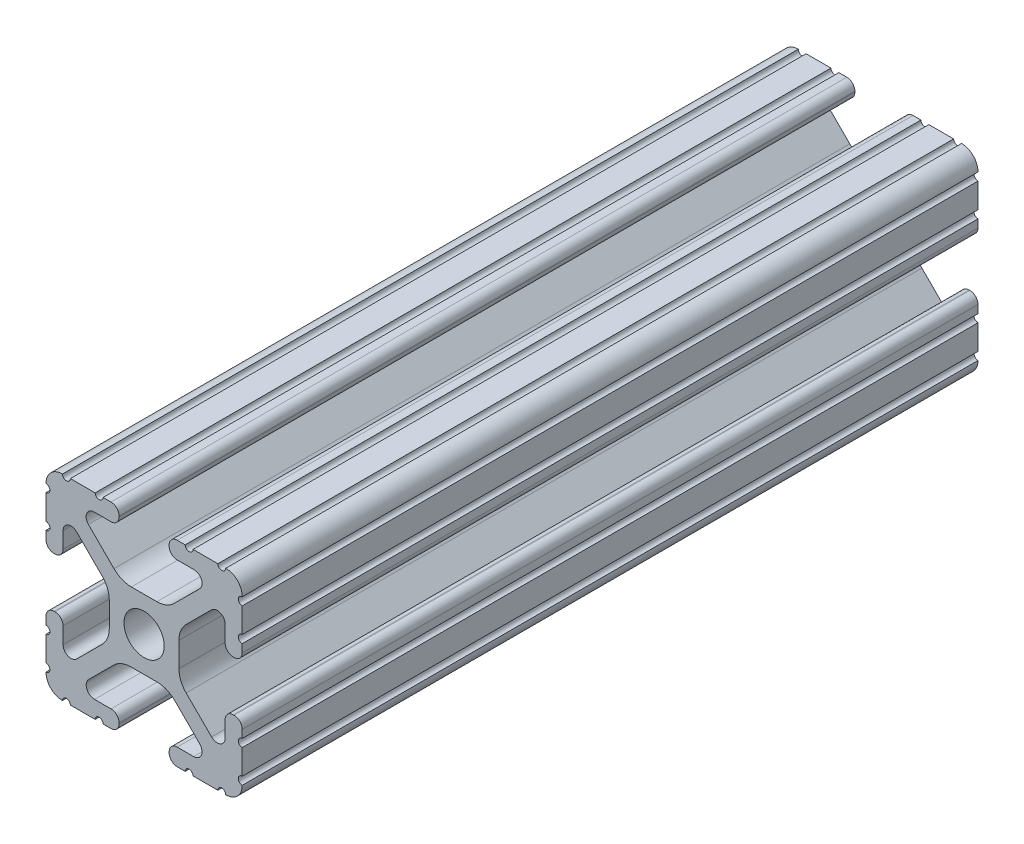
SolidWorks part; units mm, degrees
ref_plane "Front Plane" through (0, 0, 0) normal (0, 0, 1) x (1, 0, 0)
ref_plane "Top Plane" through (0, 0, 0) normal (0, 1, 0) x (1, 0, 0)
ref_plane "Right Plane" through (0, 0, 0) normal (1, 0, 0) x (0, 0, -1)
sketch "Sketch1" plane through (0, 0, 0) normal (0, 0, 1) x (1, 0, 0)
  line L88 (-7.1797, -8.6452) -> (-3.9523, -5.4237)
  line L89 (-1.7093, -4.4958) -> (1.7093, -4.4958)
  line L90 (3.9523, -5.4237) -> (7.1797, -8.6452)
  line L91 (6.4164, -10.4902) -> (4.2875, -10.4902)
  line L92 (3.2385, -11.5392) -> (3.2385, -11.651)
  line L93 (4.2875, -12.7) -> (5.3171, -12.7)
  line L94 (6.3331, -12.7) -> (9.5504, -12.7)
  line L95 (12.7, -9.5504) -> (12.7, -6.3331)
  line L96 (12.7, -5.3171) -> (12.7, -4.2875)
  line L97 (11.651, -3.2385) -> (11.5392, -3.2385)
  line L98 (10.4902, -4.2875) -> (10.4902, -6.4021)
  line L99 (8.7371, -7.1294) -> (5.441, -3.8408)
  line L100 (4.5085, -1.5932) -> (4.5085, 1.5932)
  line L101 (5.441, 3.8408) -> (8.7371, 7.1294)
  line L102 (10.4902, 6.4021) -> (10.4902, 4.2875)
  line L103 (11.5392, 3.2385) -> (11.651, 3.2385)
  line L104 (12.7, 4.2875) -> (12.7, 5.3171)
  line L105 (12.7, 6.3331) -> (12.7, 9.5504)
  line L106 (9.5504, 12.7) -> (6.3331, 12.7)
  line L107 (5.3171, 12.7) -> (4.2875, 12.7)
  line L108 (3.2385, 11.651) -> (3.2385, 11.5392)
  line L109 (4.2875, 10.4902) -> (6.4768, 10.4902)
  line L110 (7.207, 8.7244) -> (3.8983, 5.4232)
  line L111 (1.6558, 4.4958) -> (-1.6558, 4.4958)
  line L112 (-3.8983, 5.4232) -> (-7.207, 8.7244)
  line L113 (-6.4768, 10.4902) -> (-4.2875, 10.4902)
  line L114 (-3.2385, 11.5392) -> (-3.2385, 11.651)
  line L115 (-4.2875, 12.7) -> (-5.3171, 12.7)
  line L116 (-6.3331, 12.7) -> (-9.5504, 12.7)
  line L117 (-12.7, 9.5504) -> (-12.7, 6.3331)
  line L118 (-12.7, 5.3171) -> (-12.7, 4.2875)
  line L119 (-11.651, 3.2385) -> (-11.5392, 3.2385)
  line L120 (-10.4902, 4.2875) -> (-10.4902, 6.4021)
  line L121 (-8.7371, 7.1294) -> (-5.441, 3.8408)
  line L122 (-4.5085, 1.5932) -> (-4.5085, -1.5932)
  line L123 (-5.441, -3.8408) -> (-8.7371, -7.1294)
  line L124 (-10.4902, -6.4021) -> (-10.4902, -4.2875)
  line L125 (-11.5392, -3.2385) -> (-11.651, -3.2385)
  line L126 (-12.7, -4.2875) -> (-12.7, -5.3171)
  line L127 (-12.7, -6.3331) -> (-12.7, -9.5504)
  line L128 (-9.5504, -12.7) -> (-6.3331, -12.7)
  line L129 (-5.3171, -12.7) -> (-4.2875, -12.7)
  line L130 (-3.2385, -11.651) -> (-3.2385, -11.5392)
  line L131 (-4.2875, -10.4902) -> (-6.4164, -10.4902)
  circle A1 centre (0, 0) radius 2.6035
  arc A104 (-7.1797, -8.6452) -> (-6.4164, -10.4902) centre (-6.4164, -9.4098) ccw
  arc A105 (-1.7093, -4.4958) -> (-3.9523, -5.4237) centre (-1.7093, -7.6708) ccw
  arc A106 (3.9523, -5.4237) -> (1.7093, -4.4958) centre (1.7093, -7.6708) ccw
  arc A107 (6.4164, -10.4902) -> (7.1797, -8.6452) centre (6.4164, -9.4098) ccw
  arc A108 (4.2875, -10.4902) -> (3.2385, -11.5392) centre (4.2875, -11.5392) ccw
  arc A109 (3.2385, -11.651) -> (4.2875, -12.7) centre (4.2875, -11.651) ccw
  arc A110 (6.3331, -12.7) -> (5.3171, -12.7) centre (5.8251, -12.7) ccw
  arc A111 (10.5664, -12.6998) -> (9.5504, -12.7) centre (10.0584, -12.7) ccw
  arc A112 (10.5664, -12.6998) -> (12.6998, -10.5664) centre (10.5918, -10.5918) ccw
  arc A113 (12.7, -9.5504) -> (12.6998, -10.5664) centre (12.7, -10.0584) ccw
  arc A114 (12.7, -5.3171) -> (12.7, -6.3331) centre (12.7, -5.8251) ccw
  arc A115 (12.7, -4.2875) -> (11.651, -3.2385) centre (11.651, -4.2875) ccw
  arc A116 (11.5392, -3.2385) -> (10.4902, -4.2875) centre (11.5392, -4.2875) ccw
  arc A117 (8.7371, -7.1294) -> (10.4902, -6.4021) centre (9.4628, -6.4021) ccw
  arc A118 (4.5085, -1.5932) -> (5.441, -3.8408) centre (7.6835, -1.5932) ccw
  arc A119 (5.441, 3.8408) -> (4.5085, 1.5932) centre (7.6835, 1.5932) ccw
  arc A120 (10.4902, 6.4021) -> (8.7371, 7.1294) centre (9.4628, 6.4021) ccw
  arc A121 (10.4902, 4.2875) -> (11.5392, 3.2385) centre (11.5392, 4.2875) ccw
  arc A122 (11.651, 3.2385) -> (12.7, 4.2875) centre (11.651, 4.2875) ccw
  arc A123 (12.7, 6.3331) -> (12.7, 5.3171) centre (12.7, 5.8251) ccw
  arc A124 (12.6998, 10.5664) -> (12.7, 9.5504) centre (12.7, 10.0584) ccw
  arc A125 (12.6998, 10.5664) -> (10.5664, 12.6998) centre (10.5918, 10.5918) ccw
  arc A126 (9.5504, 12.7) -> (10.5664, 12.6998) centre (10.0584, 12.7) ccw
  arc A127 (5.3171, 12.7) -> (6.3331, 12.7) centre (5.8251, 12.7) ccw
  arc A128 (4.2875, 12.7) -> (3.2385, 11.651) centre (4.2875, 11.651) ccw
  arc A129 (3.2385, 11.5392) -> (4.2875, 10.4902) centre (4.2875, 11.5392) ccw
  arc A130 (7.207, 8.7244) -> (6.4768, 10.4902) centre (6.4768, 9.4563) ccw
  arc A131 (1.6558, 4.4958) -> (3.8983, 5.4232) centre (1.6558, 7.6708) ccw
  arc A132 (-3.8983, 5.4232) -> (-1.6558, 4.4958) centre (-1.6558, 7.6708) ccw
  arc A133 (-6.4768, 10.4902) -> (-7.207, 8.7244) centre (-6.4768, 9.4563) ccw
  arc A134 (-4.2875, 10.4902) -> (-3.2385, 11.5392) centre (-4.2875, 11.5392) ccw
  arc A135 (-3.2385, 11.651) -> (-4.2875, 12.7) centre (-4.2875, 11.651) ccw
  arc A136 (-6.3331, 12.7) -> (-5.3171, 12.7) centre (-5.8251, 12.7) ccw
  arc A137 (-10.5664, 12.6998) -> (-9.5504, 12.7) centre (-10.0584, 12.7) ccw
  arc A138 (-10.5664, 12.6998) -> (-12.6998, 10.5664) centre (-10.5918, 10.5918) ccw
  arc A139 (-12.7, 9.5504) -> (-12.6998, 10.5664) centre (-12.7, 10.0584) ccw
  arc A140 (-12.7, 5.3171) -> (-12.7, 6.3331) centre (-12.7, 5.8251) ccw
  arc A141 (-12.7, 4.2875) -> (-11.651, 3.2385) centre (-11.651, 4.2875) ccw
  arc A142 (-11.5392, 3.2385) -> (-10.4902, 4.2875) centre (-11.5392, 4.2875) ccw
  arc A143 (-8.7371, 7.1294) -> (-10.4902, 6.4021) centre (-9.4628, 6.4021) ccw
  arc A144 (-4.5085, 1.5932) -> (-5.441, 3.8408) centre (-7.6835, 1.5932) ccw
  arc A145 (-5.441, -3.8408) -> (-4.5085, -1.5932) centre (-7.6835, -1.5932) ccw
  arc A146 (-10.4902, -6.4021) -> (-8.7371, -7.1294) centre (-9.4628, -6.4021) ccw
  arc A147 (-10.4902, -4.2875) -> (-11.5392, -3.2385) centre (-11.5392, -4.2875) ccw
  arc A148 (-11.651, -3.2385) -> (-12.7, -4.2875) centre (-11.651, -4.2875) ccw
  arc A149 (-12.7, -6.3331) -> (-12.7, -5.3171) centre (-12.7, -5.8251) ccw
  arc A150 (-12.6998, -10.5664) -> (-12.7, -9.5504) centre (-12.7, -10.0584) ccw
  arc A151 (-12.6998, -10.5664) -> (-10.5664, -12.6998) centre (-10.5918, -10.5918) ccw
  arc A152 (-9.5504, -12.7) -> (-10.5664, -12.6998) centre (-10.0584, -12.7) ccw
  arc A153 (-5.3171, -12.7) -> (-6.3331, -12.7) centre (-5.8251, -12.7) ccw
  arc A154 (-4.2875, -12.7) -> (-3.2385, -11.651) centre (-4.2875, -11.651) ccw
  arc A155 (-3.2385, -11.5392) -> (-4.2875, -10.4902) centre (-4.2875, -11.5392) ccw
extrude "Boss-Extrude1" add sketch "Sketch1" along normal mid plane 95.25
